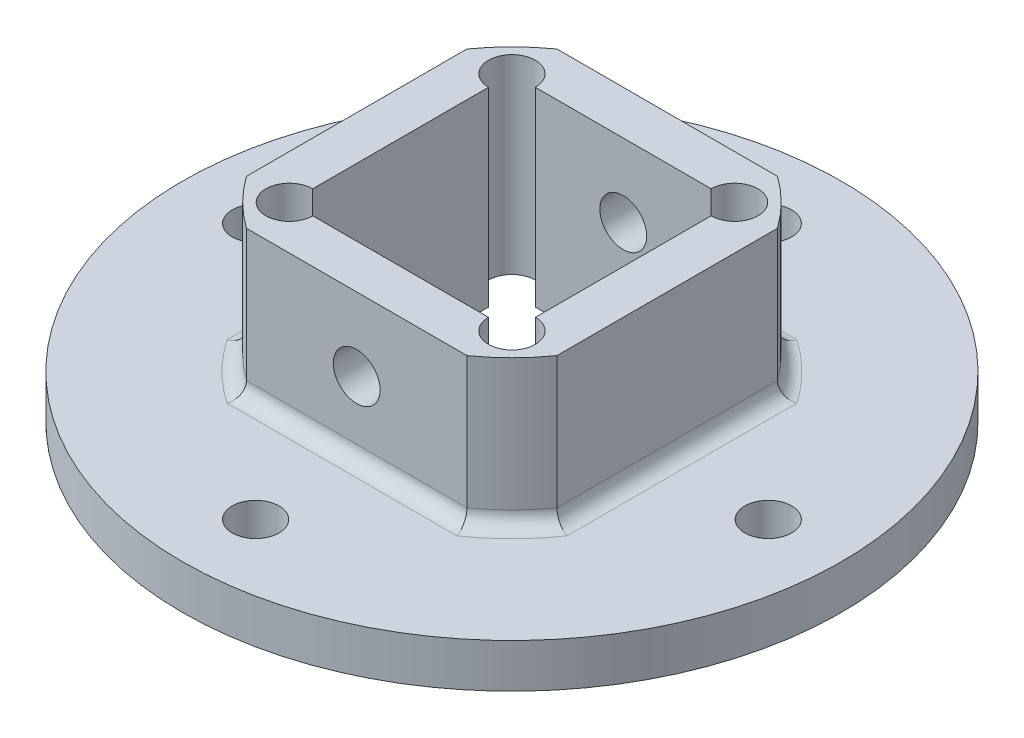
SolidWorks part; units mm, degrees
material "ABS"
ref_plane "前视基准面" through (0, 0, 0) normal (0, 0, 1) x (1, 0, 0)
ref_plane "上视基准面" through (0, 0, 0) normal (0, 1, 0) x (1, 0, 0)
ref_plane "右视基准面" through (0, 0, 0) normal (1, 0, 0) x (0, 0, -1)
other "Configuration Table"
sketch "草图1" plane through (0, 0, 0) normal (0, 1, 0) x (1, 0, 0)
  line L1 (-7.6, -7.6) -> (7.6, -7.6)
  line L2 (-7.6, -7.6) -> (-7.6, 7.6)
  line L3 (-7.6, 7.6) -> (7.6, 7.6)
  line L4 (7.6, -7.6) -> (7.6, 7.6)
  line L5 (-7.6, -7.6) -> (7.6, 7.6) construction
  line L6 (-7.6, 7.6) -> (7.6, -7.6) construction
  circle A0 centre (0, 0) radius 22.5
  circle A1 centre (0, 0) radius 17.5 construction
  circle A2 centre (0, 17.5) radius 1.6
  circle A3 centre (17.5, 0) radius 1.6
  circle A4 centre (0, 0) radius 17.5 construction
  circle A5 centre (0, -17.5) radius 1.6
  circle A6 centre (0, 0) radius 17.5 construction
  circle A7 centre (-17.5, 0) radius 1.6
  circle A8 centre (0, 0) radius 17.5 construction
  point P18 (0, 0)
  dimension "D1" = 45
  dimension "D2" = 35
  dimension "D3" = 1.6
  dimension "D5" = 15.2
  dimension "D4" = 4
extrude "凸台-拉伸1" add sketch "草图1" along normal blind 3
sketch "草图2" plane through (0, 3, 0) normal (0, 1, 0) x (1, 0, 0)
  line L1 (-10.6, -7.526) -> (-10.6, 7.526)
  line L2 (-7.6, -7.6) -> (7.6, -7.6)
  line L3 (-7.6, -7.6) -> (-7.6, 7.6)
  line L4 (-7.6, 7.6) -> (7.6, 7.6)
  line L5 (7.6, -7.6) -> (7.6, 7.6)
  line L6 (-7.6, -7.6) -> (7.6, 7.6) construction
  line L7 (-7.6, 7.6) -> (7.6, -7.6) construction
  line L8 (-7.526, 10.6) -> (7.526, 10.6)
  line L9 (10.6, -7.526) -> (10.6, 7.526)
  line L10 (-7.526, -10.6) -> (7.526, -10.6)
  line L11 (-10.6, 10.6) -> (10.6, 10.6) construction
  line L12 (10.6, -10.6) -> (10.6, 10.6) construction
  line L13 (-10.6, -10.6) -> (10.6, -10.6) construction
  line L14 (-10.6, -10.6) -> (-10.6, 10.6) construction
  arc A0 (10.6, 7.526) -> (7.526, 10.6) centre (0, 0) ccw
  arc A1 (7.526, -10.6) -> (10.6, -7.526) centre (0, 0) ccw
  arc A2 (-10.6, -7.526) -> (-7.526, -10.6) centre (0, 0) ccw
  arc A3 (-7.526, 10.6) -> (-10.6, 7.526) centre (0, 0) ccw
  point P2 (0, 0)
  dimension "D3" = 26
  dimension "D1" = 15.2
  dimension "D2" = 3
extrude "凸台-拉伸2" add sketch "草图2" along normal blind 10
sketch "草图3" plane through (0, 0, -10.6) normal (0, 0, -1) x (-1, 0, 0)
  line L0 (0, 13) -> (0, 0) construction
  line L1 (-7.526, 13) -> (7.526, 13) construction
  circle A0 centre (0, 8) radius 1.6
  dimension "D1" = 3.2
  dimension "D2" = 5
extrude "切除-拉伸1" cut sketch "草图3" against normal through all
fillet "圆角1" radius 1 8 edges at (-9.1924, 3, 9.1924) (9.1924, 3, 9.1924) (0, 3, 10.6) (10.6, 3, 0) (9.1924, 3, -9.1924) (-9.1924, 3, -9.1924) (0, 3, -10.6) (-10.6, 3, 0)
sketch "草图4" plane through (0, 13, 0) normal (0, 1, 0) x (1, 0, 0)
  circle A0 centre (7.6, 7.6) radius 1.6
  circle A1 centre (7.6, -7.6) radius 1.6
  circle A2 centre (-7.6, -7.6) radius 1.6
  circle A3 centre (-7.6, 7.6) radius 1.6
  dimension "D1" = 3.2
  dimension "D2" = 3.2
  dimension "D3" = 3.2
  dimension "D4" = 3.2
extrude "切除-拉伸2" cut sketch "草图4" against normal through all
